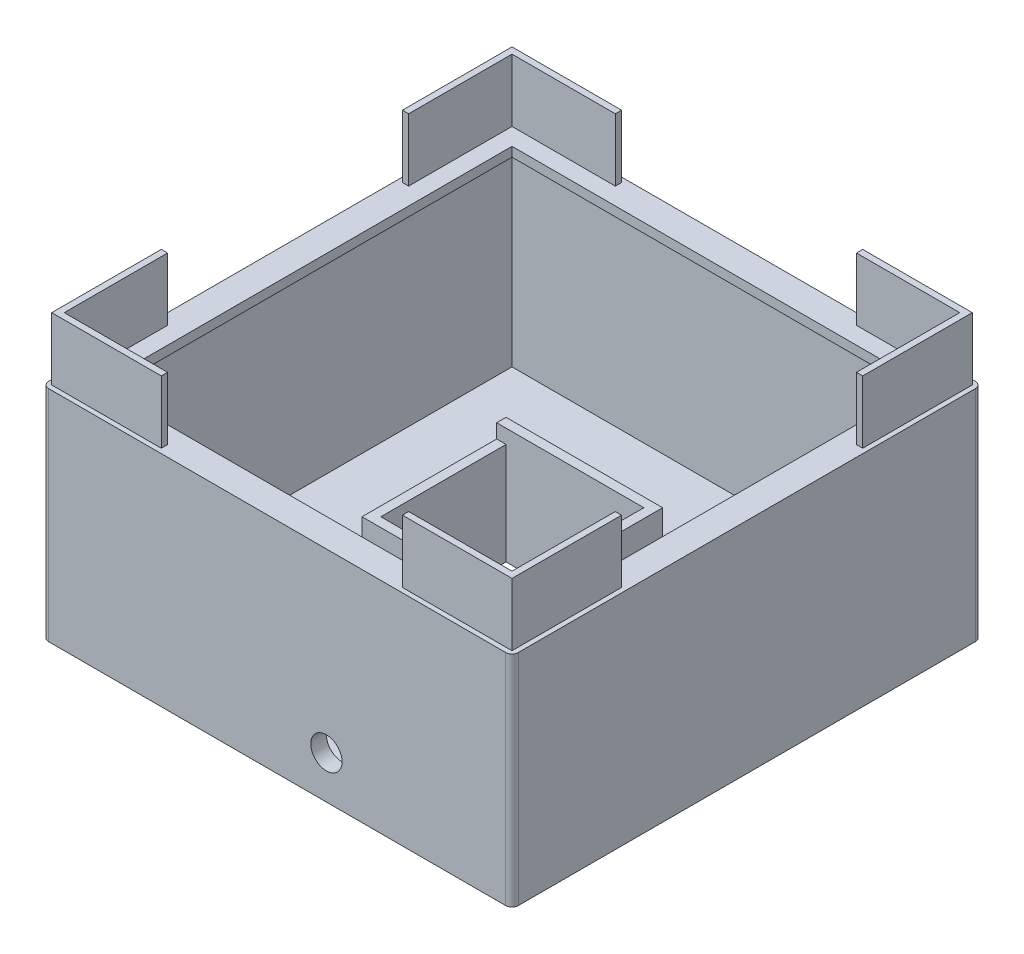
SolidWorks part; units mm, degrees
ref_plane "Front Plane" through (0, 0, 0) normal (0, 0, 1) x (1, 0, 0)
ref_plane "Top Plane" through (0, 0, 0) normal (0, 1, 0) x (1, 0, 0)
ref_plane "Right Plane" through (0, 0, 0) normal (1, 0, 0) x (0, 0, -1)
sketch "Sketch1" plane through (0, 0, 0) normal (0, 1, 0) x (1, 0, 0)
  line L1 (0, 0) -> (150, 0)
  line L2 (0, 0) -> (0, 150)
  line L3 (0, 150) -> (150, 150)
  line L4 (150, 0) -> (150, 150)
  dimension "D1" = 150
  dimension "D2" = 150
extrude "Boss-Extrude1" add sketch "Sketch1" along normal blind 70 contours L2 L3 L4 L1
shell "Shell1" thickness 5
sketch "Sketch2" plane through (0, 5, 0) normal (0, 1, 0) x (1, 0, 0)
  line L0 (50, 98.1) -> (50, 52.1)
  line L1 (53, 95.1) -> (97, 95.1)
  line L2 (53, 95.1) -> (53, 55.1)
  line L3 (53, 55.1) -> (97, 55.1)
  line L4 (97, 95.1) -> (97, 55.1)
  line L5 (50, 52.1) -> (100, 52.1)
  line L6 (100, 98.1) -> (100, 52.1)
  line L7 (50, 98.1) -> (100, 98.1)
  line L8 (5, 5) -> (145, 5) construction
  line L9 (5, 5) -> (5, 145) construction
  dimension "D1" = 40
  dimension "D2" = 3
  dimension "D3" = 3
  dimension "D4" = 3
  dimension "D5" = 3
  dimension "D6" = 47.1
  dimension "D7" = 50
  dimension "D8" = 45
extrude "Boss-Extrude2" add sketch "Sketch2" along normal blind 32
sketch "Sketch5" plane through (0, 5, 0) normal (0, 1, 0) x (1, 0, 0)
  line L1 (53, 95.1) -> (97, 95.1)
  line L2 (53, 95.1) -> (53, 55.1)
  line L3 (53, 55.1) -> (97, 55.1)
  line L4 (97, 95.1) -> (97, 55.1)
extrude "Cut-Extrude4" cut sketch "Sketch5" against normal up to next
sketch "Sketch6" plane through (0, 70, 0) normal (0, 1, 0) x (1, 0, 0)
  line L0 (1.5, 148.5) -> (36.5, 148.5)
  line L1 (36.5, 148.5) -> (36.5, 146.5)
  line L2 (36.5, 146.5) -> (3.5, 146.5)
  line L3 (3.5, 146.5) -> (3.5, 113.5)
  line L4 (3.5, 113.5) -> (1.5, 113.5)
  line L5 (1.5, 113.5) -> (1.5, 148.5)
  line L6 (1.5, 148.5) -> (36.5, 148.5)
  line L7 (75, 210.1582) -> (75, 50.1582) construction
  line L8 (-21.9429, 75) -> (138.0571, 75) construction
  line L9 (148.5, 113.5) -> (148.5, 148.5)
  line L10 (146.5, 113.5) -> (148.5, 113.5)
  line L11 (36.5, 148.5) -> (36.5, 146.5)
  line L12 (36.5, 146.5) -> (3.5, 146.5)
  line L13 (3.5, 146.5) -> (3.5, 113.5)
  line L14 (3.5, 113.5) -> (1.5, 113.5)
  line L15 (1.5, 113.5) -> (1.5, 148.5)
  line L16 (146.5, 146.5) -> (146.5, 113.5)
  line L17 (113.5, 146.5) -> (146.5, 146.5)
  line L18 (113.5, 148.5) -> (113.5, 146.5)
  line L19 (148.5, 148.5) -> (113.5, 148.5)
  line L20 (148.5, 113.5) -> (148.5, 148.5)
  line L21 (146.5, 113.5) -> (148.5, 113.5)
  line L22 (146.5, 146.5) -> (146.5, 113.5)
  line L23 (113.5, 146.5) -> (146.5, 146.5)
  line L24 (113.5, 148.5) -> (113.5, 146.5)
  line L25 (148.5, 148.5) -> (113.5, 148.5)
  line L26 (148.5, 1.5) -> (113.5, 1.5)
  line L27 (113.5, 1.5) -> (113.5, 3.5)
  line L28 (113.5, 3.5) -> (146.5, 3.5)
  line L29 (146.5, 3.5) -> (146.5, 36.5)
  line L30 (146.5, 36.5) -> (148.5, 36.5)
  line L31 (148.5, 36.5) -> (148.5, 1.5)
  line L32 (148.5, 1.5) -> (113.5, 1.5)
  line L33 (113.5, 1.5) -> (113.5, 3.5)
  line L34 (113.5, 3.5) -> (146.5, 3.5)
  line L35 (146.5, 3.5) -> (146.5, 36.5)
  line L36 (1.5, 36.5) -> (1.5, 1.5)
  line L37 (3.5, 36.5) -> (1.5, 36.5)
  line L38 (3.5, 3.5) -> (3.5, 36.5)
  line L39 (36.5, 3.5) -> (3.5, 3.5)
  line L40 (36.5, 1.5) -> (36.5, 3.5)
  line L41 (146.5, 36.5) -> (148.5, 36.5)
  line L42 (148.5, 36.5) -> (148.5, 1.5)
  line L43 (1.5, 1.5) -> (36.5, 1.5)
  line L44 (1.5, 36.5) -> (1.5, 1.5)
  line L45 (3.5, 36.5) -> (1.5, 36.5)
  line L46 (3.5, 3.5) -> (3.5, 36.5)
  line L47 (36.5, 3.5) -> (3.5, 3.5)
  line L48 (36.5, 1.5) -> (36.5, 3.5)
  line L49 (1.5, 1.5) -> (36.5, 1.5)
  line L50 (0, 0) -> (0, 150) construction
  line L51 (0, 150) -> (150, 150) construction
  line L52 (0, 0) -> (150, 0) construction
  line L53 (145, 5) -> (145, 145) construction
  dimension "D1" = 2
  dimension "D2" = 35
  dimension "D3" = 35
  dimension "D4" = 2
  dimension "D5" = 1.5
  dimension "D6" = 1.5
  dimension "D7" = 1.5
  dimension "D8" = 1.5
extrude "Boss-Extrude3" add sketch "Sketch6" along normal blind 20 contours L5 L4 L3 L2 L1 L0 | L36 L43 L40 L39 L38 L37 | L31 L30 L29 L28 L27 L26 | L9 L19 L18 L17 L16 L10
sketch "Sketch7" plane through (0, 70, 0) normal (0, 1, 0) x (1, 0, 0)
  line L0 (9, 141) -> (9, 9)
  line L1 (5, 145) -> (145, 145)
  line L2 (5, 145) -> (5, 5)
  line L3 (5, 5) -> (145, 5)
  line L4 (145, 145) -> (145, 5)
  line L5 (9, 9) -> (141, 9)
  line L6 (141, 141) -> (141, 9)
  line L7 (9, 141) -> (141, 141)
  dimension "D1" = 4
extrude "Boss-Extrude4" add sketch "Sketch7" against normal blind 3
sketch "Sketch9" plane through (100, 0, 0) normal (1, 0, 0) x (0, 0, -1)
  line L0 (68.1, 37) -> (82.1, 37)
  line L1 (68.1, 37) -> (68.1, 21.2)
  line L2 (68.1, 21.2) -> (82.1, 21.2)
  line L3 (82.1, 37) -> (82.1, 21.2)
  line L4 (52.1, 37) -> (52.1, 5) construction
  dimension "D2" = 14
  dimension "D3" = 16
extrude "Cut-Extrude5" cut sketch "Sketch9" against normal up to next
sketch "Sketch10" plane through (100, 0, 0) normal (1, 0, 0) x (0, 0, -1)
  line L1 (68.1, 21.2) -> (82.1, 21.2)
  line L2 (68.1, 21.2) -> (68.1, 17.6125)
  line L3 (68.1, 17.6125) -> (82.1, 17.6125)
  line L4 (82.1, 21.2) -> (82.1, 17.6125)
  dimension "D1" = 3.5875
extrude "Boss-Extrude5" add sketch "Sketch10" along normal blind 3.5
sketch "Sketch11" plane through (0, 21.2, 0) normal (0, 1, 0) x (1, 0, 0)
  line L0 (103.5, 82.1) -> (103.5, 68.1) construction
  line L2 (103.5, 82.1) -> (100, 82.1) construction
  circle A0 centre (101.26, 75.55) radius 1.1
  dimension "D1" = 2.2
  dimension "D2" = 2.24
  dimension "D3" = 6.55
extrude "Cut-Extrude6" cut sketch "Sketch11" against normal up to next
sketch "Sketch12" plane through (0, 37, 0) normal (0, 1, 0) x (1, 0, 0)
  line L0 (53, 95.1) -> (50, 95.1)
  line L1 (50, 98.1) -> (50, 52.1) construction
  line L2 (50, 95.1) -> (50, 52.1)
  line L3 (50, 52.1) -> (100, 52.1)
  line L4 (100, 52.1) -> (100, 68.1)
  line L5 (100, 68.1) -> (97, 68.1)
  line L6 (97, 68.1) -> (97, 55.1)
  line L7 (97, 55.1) -> (53, 55.1)
  line L8 (53, 55.1) -> (53, 95.1)
extrude "Cut-Extrude8" cut sketch "Sketch12" against normal blind 4.5
fillet "Fillet1" radius 2 4 edges at (150, 35, -150) (150, 35, 0) (0, 35, -150) (0, 35, 0)
sketch "Sketch13" plane through (0, 0, 0) normal (0, -1, 0) x (1, 0, 0)
  line L0 (1.5, -1.5) -> (36.6, -1.5)
  line L1 (36.6, -1.5) -> (36.6, -3.6)
  line L2 (36.6, -3.6) -> (3.6, -3.6)
  line L3 (3.6, -3.6) -> (3.6, -36.6)
  line L4 (3.6, -36.6) -> (1.5, -36.6)
  line L5 (1.5, -36.6) -> (1.5, -1.5)
  line L6 (75, -1.7211) -> (75, -151.7211) construction
  line L7 (4.6614, -75) -> (154.6614, -75) construction
  line L8 (148.5, -36.6) -> (148.5, -1.5)
  line L9 (146.4, -36.6) -> (148.5, -36.6)
  line L10 (146.4, -3.6) -> (146.4, -36.6)
  line L11 (113.4, -3.6) -> (146.4, -3.6)
  line L12 (113.4, -1.5) -> (113.4, -3.6)
  line L13 (148.5, -1.5) -> (113.4, -1.5)
  line L14 (148.5, -148.5) -> (113.4, -148.5)
  line L15 (113.4, -148.5) -> (113.4, -146.4)
  line L16 (113.4, -146.4) -> (146.4, -146.4)
  line L17 (146.4, -146.4) -> (146.4, -113.4)
  line L18 (146.4, -113.4) -> (148.5, -113.4)
  line L19 (148.5, -113.4) -> (148.5, -148.5)
  line L20 (1.5, -113.4) -> (1.5, -148.5)
  line L21 (3.6, -113.4) -> (1.5, -113.4)
  line L22 (3.6, -146.4) -> (3.6, -113.4)
  line L23 (36.6, -146.4) -> (3.6, -146.4)
  line L24 (36.6, -148.5) -> (36.6, -146.4)
  line L25 (1.5, -148.5) -> (36.6, -148.5)
  line L26 (0, -2) -> (0, -148) construction
  line L27 (2, 0) -> (148, 0) construction
  line L28 (150, -2) -> (150, -148) construction
  line L29 (2, -150) -> (148, -150) construction
  dimension "D1" = 2.1
  dimension "D2" = 2.1
  dimension "D3" = 35.1
  dimension "D4" = 35.1
  dimension "D5" = 1.5
  dimension "D6" = 1.5
  dimension "D7" = 1.5
  dimension "D8" = 1.5
extrude "Cut-Extrude9" cut sketch "Sketch13" against normal blind 20.1
sketch "Sketch14" plane through (0, 0, -5) normal (0, 0, -1) x (-1, 0, 0)
  circle A0 centre (-90.7314, 13.6153) radius 5
extrude "Cut-Extrude11" cut sketch "Sketch14" against normal blind 20.1
